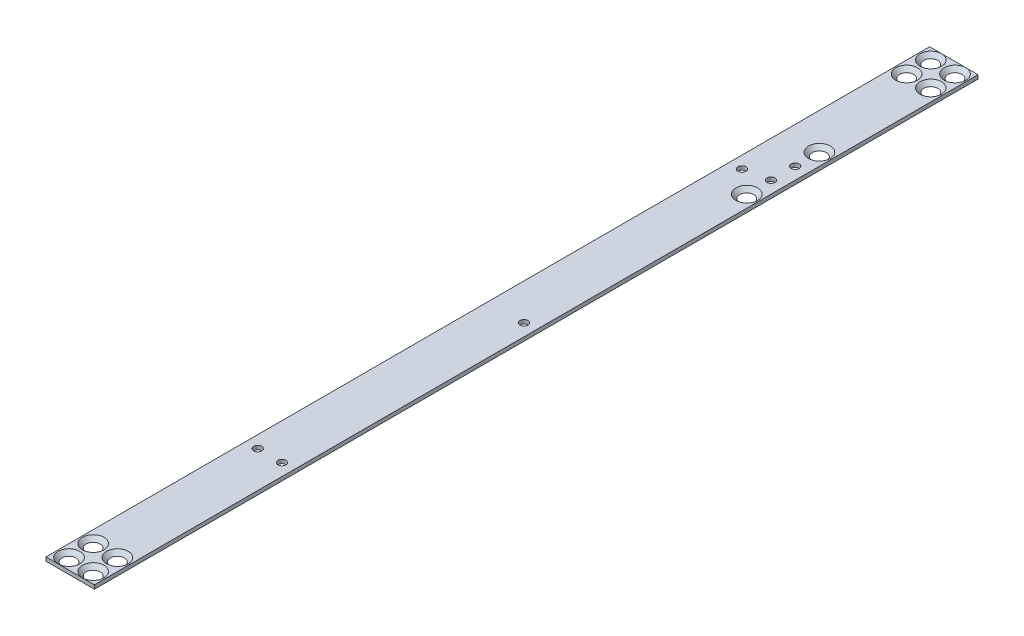
SolidWorks part; units mm, degrees
ref_plane "Front Plane" through (0, 0, 0) normal (0, 0, 1) x (1, 0, 0)
ref_plane "Top Plane" through (0, 0, 0) normal (0, 1, 0) x (1, 0, 0)
ref_plane "Right Plane" through (0, 0, 0) normal (1, 0, 0) x (0, 0, -1)
sketch "Sketch1" plane through (0, 0, 0) normal (0, 1, 0) x (1, 0, 0)
  line L1 (-10, -182.5) -> (10, -182.5)
  line L2 (-10, -182.5) -> (-10, 182.5)
  line L3 (-10, 182.5) -> (10, 182.5)
  line L4 (10, -182.5) -> (10, 182.5)
  line L5 (-10, -182.5) -> (10, 182.5) construction
  line L6 (-10, 182.5) -> (10, -182.5) construction
  point P1 (0, 0)
  dimension "D1" = 365
  dimension "D2" = 20
extrude "Boss-Extrude1" add sketch "Sketch1" along normal blind 1.5875
hole_wizard "CSK for M4 SFHCS1" positions "Sketch2" profile "Sketch3" countersink size "M4" standard "ANSI Metric" end condition through all
sketch "Sketch2" plane through (0, 1.5875, 0) normal (0, 1, 0) x (1, 0, 0)
  line L1 (-5, -178) -> (5, -178)
  line L2 (-5, -178) -> (-5, -168)
  line L3 (-5, -168) -> (5, -168)
  line L4 (5, -178) -> (5, -168)
  line L5 (-5, -178) -> (5, -168) construction
  line L6 (-5, -168) -> (5, -178) construction
  line L7 (-10, -182.5) -> (10, -182.5) construction
  line L8 (-10, 182.5) -> (-10, -182.5) construction
  line L9 (-0.8731, 0) -> (0.8731, 0) construction
  line L10 (-5, 168) -> (5, 178) construction
  line L11 (-5, 178) -> (5, 168) construction
  line L12 (5, 178) -> (5, 168)
  line L13 (-5, 168) -> (5, 168)
  line L14 (-5, 178) -> (-5, 168)
  line L15 (-5, 178) -> (5, 178)
  line L16 (5, 92) -> (5, 122)
  line L18 (10, 182.5) -> (-10, 182.5) construction
  point P2 (5, -168)
  point P37 (-5, -178)
  point P38 (-5, -168)
  point P39 (5, -178)
  point P45 (0, -173)
  point P54 (5, 178)
  point P55 (-5, 168)
  point P56 (-5, 178)
  point P57 (5, 168)
  point P58 (5, 92)
  point P59 (5, 122)
  point P62 (5, 107)
  dimension "D1" = 10
  dimension "D2" = 4.5
  dimension "D3" = 10
  dimension "D4" = 75.5
  dimension "D5" = 30
sketch "Sketch3" plane through (5, 1.5875, 168) normal (1, 0, 0) x (0, 0, 1)
  line L0 (0, 0) -> (0, 1.5875)
  line L1 (0, 1.5875) -> (2.25, 1.5875)
  line L2 (2.25, 1.5875) -> (2.25, 2.23)
  line L3 (2.25, 2.23) -> (4.48, 0)
  line L5 (4.48, 0) -> (0, 0)
  line L6 (-2.25, 2.23) -> (-4.48, 0) construction
  line L11 (0, -6.35) -> (0, 107.95) construction
  dimension "Thru Hole Dia." = 4.5
  dimension "Thru Hole Depth" = 1.5875
  dimension "Near C'Sink Dia." = 8.96
  dimension "Near C'Sink Angle" = 90
hole_wizard "M4x0.7 Tapped Hole1" positions "Sketch4" profile "Sketch6" tap size "M4x0.7" standard "ANSI Metric" end condition through all
sketch "Sketch4" plane through (0, 1.5875, 0) normal (0, 1, 0) x (1, 0, 0)
  line L0 (-5, -100) -> (-5, 100)
  line L2 (-10, 182.5) -> (-10, -182.5) construction
  line L3 (0, -0.8731) -> (0, 0.8731) construction
  line L5 (5, -100) -> (5, 0)
  line L6 (5, 102) -> (5, 112)
  line L8 (10, 182.5) -> (-10, 182.5) construction
  point P1 (-5, -100)
  point P2 (-5, 100)
  point P6 (-5, 0)
  point P19 (5, -100)
  point P24 (5, 0)
  point P29 (5, 102)
  point P30 (5, 112)
  point P33 (5, 107)
  dimension "D1" = 200
  dimension "D2" = 5
  dimension "D3" = 100
  dimension "D4" = 10
  dimension "D5" = 75.5
sketch "Sketch6" plane through (-5, 1.5875, 100) normal (1, 0, 0) x (0, 0, 1)
  line L0 (0, 0) -> (0, 1.5875)
  line L1 (0, 1.5875) -> (1.65, 1.5875)
  line L2 (1.65, 1.5875) -> (1.65, 0)
  line L5 (1.65, 0) -> (0, 0)
  line L11 (0, -6.35) -> (0, 107.95) construction
  dimension "Thru Tap Drill Dia." = 3.3
  dimension "Thru Tap Drill Depth" = 1.5875
cosmetic thread "Hole Thread1"
cosmetic thread "Hole Thread2"
cosmetic thread "Hole Thread3"
cosmetic thread "Hole Thread4"
cosmetic thread "Hole Thread5"
cosmetic thread "Hole Thread6"
